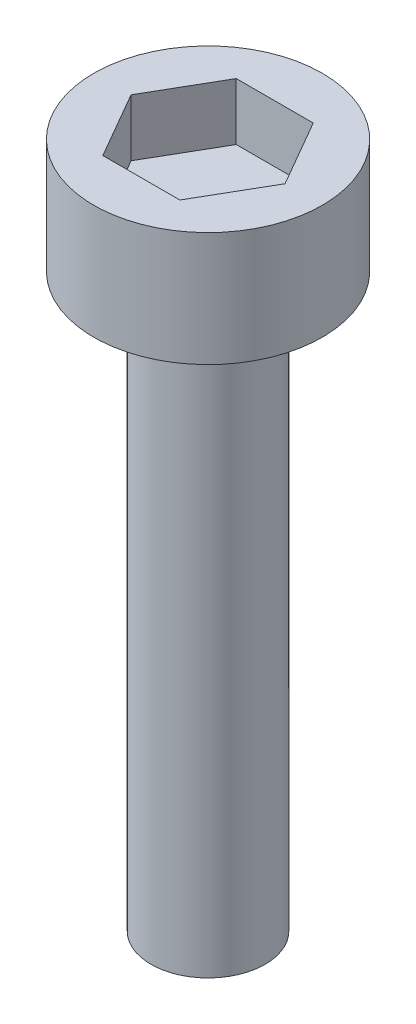
SolidWorks part; units mm, degrees
ref_plane "Front Plane" through (0, 0, 0) normal (0, 0, 1) x (1, 0, 0)
ref_plane "Top Plane" through (0, 0, 0) normal (0, 1, 0) x (1, 0, 0)
ref_plane "Right Plane" through (0, 0, 0) normal (1, 0, 0) x (0, 0, -1)
sketch "Sketch1" plane through (0, 0, 0) normal (0, 0, 1) x (1, 0, 0)
  line L0 (0, 0) -> (0, 36.502) construction
  line L1 (0, 0) -> (3, 0)
  line L2 (3, 0) -> (3, 30)
  line L3 (3, 30) -> (6, 30)
  line L4 (6, 30) -> (6, 36)
  line L5 (6, 36) -> (0, 36)
  line L6 (0, 0) -> (0, 36)
  dimension "D1" = 6
  dimension "D2" = 30
  dimension "D3" = 6
  dimension "D4" = 12
revolve "Revolve1" add sketch "Sketch1" angle 360 about L0
sketch "Sketch2" plane through (0, 36, 0) normal (0, 1, 0) x (1, 0, 0)
  line L1 (2.0207, 3.5) -> (-2.0207, 3.5)
  line L2 (-2.0207, 3.5) -> (-4.0415, 0)
  line L3 (-4.0415, 0) -> (-2.0207, -3.5)
  line L4 (-2.0207, -3.5) -> (2.0207, -3.5)
  line L5 (2.0207, -3.5) -> (4.0415, 0)
  line L6 (4.0415, 0) -> (2.0207, 3.5)
  circle A0 centre (0, 0) radius 3.5 construction
  point P1 (0, -3.5)
  dimension "D1" = 7
extrude "Cut-Extrude1" cut sketch "Sketch2" against normal blind 3
